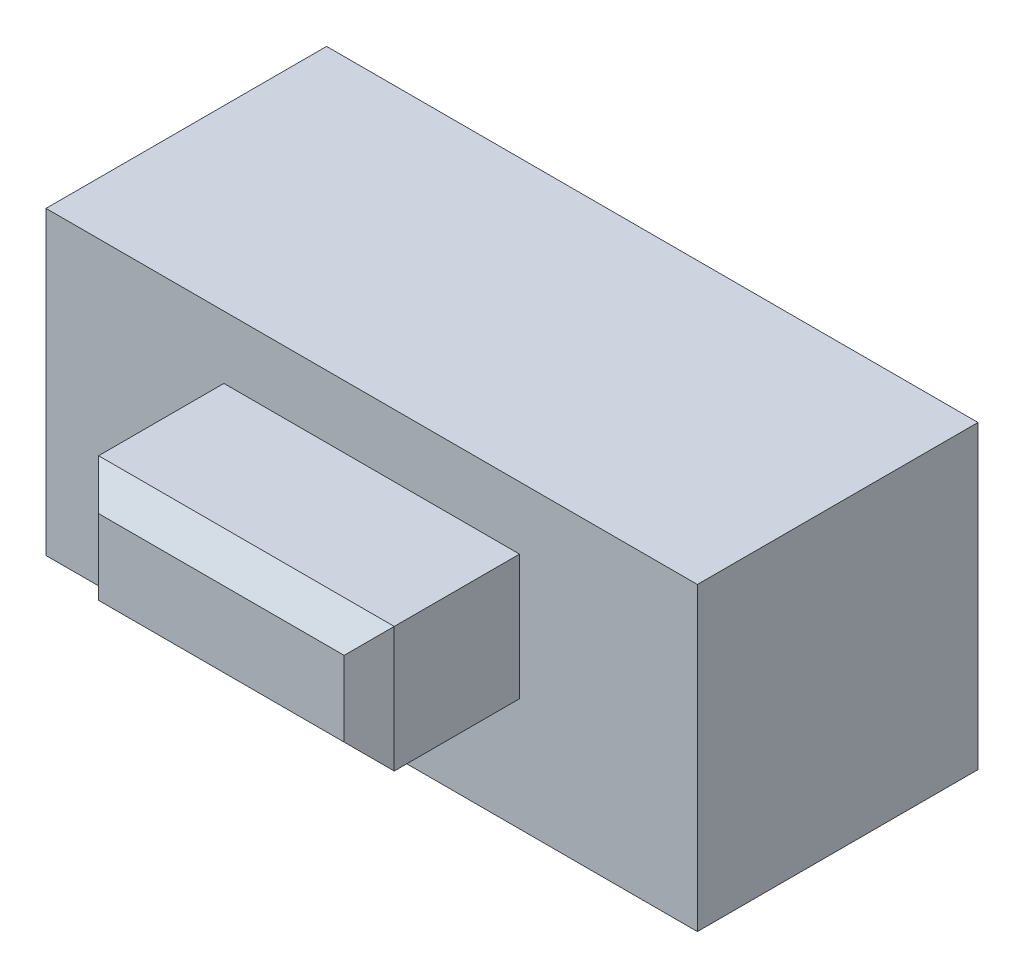
SolidWorks part; units mm, degrees
ref_plane "Front Plane" through (0, 0, 0) normal (0, 0, 1) x (1, 0, 0)
ref_plane "Top Plane" through (0, 0, 0) normal (0, 1, 0) x (1, 0, 0)
ref_plane "Right Plane" through (0, 0, 0) normal (1, 0, 0) x (0, 0, -1)
sketch "Sketch1" plane through (0, 0, 0) normal (0, 1, 0) x (1, 0, 0)
  line L1 (-6.5, -2.8) -> (6.5, -2.8)
  line L2 (-6.5, -2.8) -> (-6.5, 2.8)
  line L3 (-6.5, 2.8) -> (6.5, 2.8)
  line L4 (6.5, -2.8) -> (6.5, 2.8)
  line L5 (-6.5, -2.8) -> (6.5, 2.8) construction
  line L6 (-6.5, 2.8) -> (6.5, -2.8) construction
  point P0 (0, 0)
  dimension "D1" = 13
  dimension "D2" = 5.6
extrude "Boss-Extrude1" add sketch "Sketch1" along normal blind 6
sketch "Sketch2" plane through (0, 0, 2.8) normal (0, 0, 1) x (1, 0, 0)
  line L0 (-6.5, 0) -> (6.5, 0) construction
  line L1 (-2.95, 2.25) -> (2.95, 2.25)
  line L2 (-2.95, 2.25) -> (-2.95, 4.75)
  line L3 (-2.95, 4.75) -> (2.95, 4.75)
  line L4 (2.95, 2.25) -> (2.95, 4.75)
  line L5 (-2.95, 2.25) -> (2.95, 4.75) construction
  line L6 (-2.95, 4.75) -> (2.95, 2.25) construction
  line L7 (-6.5, 6) -> (-6.5, 0) construction
  line L8 (6.5, 6) -> (6.5, 0) construction
  point P0 (0, 3.5)
  dimension "D1" = 3.5
  dimension "D2" = 2.5
  dimension "D3" = 3.55
  dimension "D4" = 3.55
extrude "Boss-Extrude2" add sketch "Sketch2" along normal blind 3
chamfer "Chamfer1" distance 0.5 angle 45 4 edges at (2.95, 3.5, 5.8) (0, 4.75, 5.8) (-2.95, 3.5, 5.8) (0, 2.25, 5.8)
